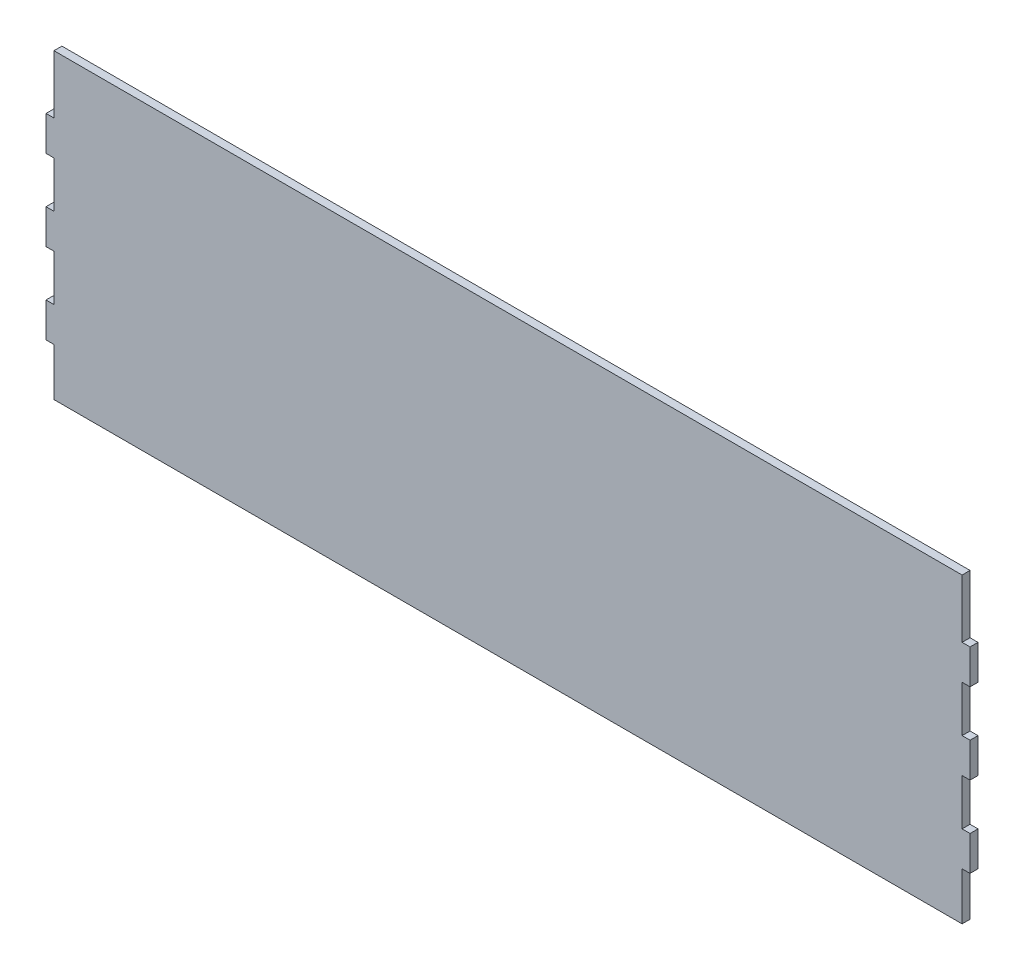
SolidWorks part; units mm, degrees
ref_plane "Front Plane" through (0, 0, 0) normal (0, 0, 1) x (1, 0, 0)
ref_plane "Top Plane" through (0, 0, 0) normal (0, 1, 0) x (1, 0, 0)
ref_plane "Right Plane" through (0, 0, 0) normal (1, 0, 0) x (0, 0, -1)
sketch "Croquis1" plane through (0, 0, 0) normal (0, 0, 1) x (1, 0, 0)
  line L1 (-174.32, 55) -> (174.32, 55)
  line L2 (-174.32, 55) -> (-174.32, -55)
  line L3 (-174.32, -55) -> (174.32, -55)
  line L4 (174.32, 55) -> (174.32, -55)
  line L5 (-174.32, 55) -> (174.32, -55) construction
  line L6 (-174.32, -55) -> (174.32, 55) construction
  point P0 (0, 0)
  dimension "D1" = 348.64
  dimension "D2" = 110
extrude "Saliente-Extruir1" add sketch "Croquis1" along normal blind 3
sketch "Croquis2" plane through (0, 0, 3) normal (0, 0, 1) x (1, 0, 0)
  line L0 (-174.32, 55) -> (-174.32, -55) construction
  line L1 (-174.32, 37) -> (-171.32, 37)
  line L2 (-174.32, 37) -> (-174.32, 23.9518)
  line L3 (-174.32, 23.9518) -> (-171.32, 23.9518)
  line L6 (-174.32, 6.5241) -> (-174.32, -6.5241)
  line L8 (-174.32, 6.5241) -> (-171.32, 6.5241)
  line L10 (-174.32, -6.5241) -> (-171.32, -6.5241)
  line L11 (-174.32, -23.9518) -> (-174.32, -37)
  line L12 (-174.32, -23.9518) -> (-171.32, -23.9518)
  line L14 (-174.32, -37) -> (-171.32, -37)
  line L15 (-174.32, -55) -> (174.32, -55) construction
  line L16 (174.32, 55) -> (-174.32, 55) construction
  line L17 (0, -55) -> (0, 55) construction
  line L18 (174.32, -23.9518) -> (171.32, -23.9518)
  line L19 (-171.32, -52) -> (171.32, -52)
  line L20 (171.32, -52) -> (171.32, 52)
  line L21 (-171.32, 52) -> (-171.32, -52)
  line L22 (171.32, 52) -> (-171.32, 52)
  line L24 (171.32, -52) -> (171.32, -37)
  line L25 (-171.32, 52) -> (-171.32, 37)
  line L28 (174.32, -37) -> (171.32, -37)
  line L29 (174.32, -23.9518) -> (174.32, -37)
  line L30 (174.32, 6.5241) -> (171.32, 6.5241)
  line L32 (174.32, -6.5241) -> (171.32, -6.5241)
  line L33 (174.32, 6.5241) -> (174.32, -6.5241)
  line L34 (174.32, 23.9518) -> (171.32, 23.9518)
  line L36 (174.32, 37) -> (171.32, 37)
  line L37 (174.32, 37) -> (174.32, 23.9518)
  line L38 (-171.32, 23.9518) -> (-171.32, 6.5241)
  line L39 (-171.32, -6.5241) -> (-171.32, -23.9518)
  line L40 (-171.32, -37) -> (-171.32, -52)
  line L41 (171.32, -23.9518) -> (171.32, -6.5241)
  line L42 (171.32, 6.5241) -> (171.32, 23.9518)
  line L43 (171.32, 37) -> (171.32, 52)
  line L44 (-171.32, 52) -> (-171.32, 55)
  line L45 (171.32, 52) -> (171.32, 55)
  line L46 (-171.32, -52) -> (-171.32, -55)
  line L47 (171.32, -52) -> (171.32, -55)
  line L48 (-171.32, -55) -> (171.32, -55)
  line L49 (-171.32, 55) -> (171.32, 55)
  line M3 (174.32, -55) -> (174.32, 55)
  line M4 (174.32, 55) -> (-174.32, 55)
  line M5 (-174.32, 55) -> (-174.32, -55)
  line M6 (-174.32, -55) -> (174.32, -55)
  dimension "D3" = 18
  dimension "D4" = 18
  dimension "D1" = 3
  dimension "D2" = 3
extrude "Cortar-Extruir1" cut sketch "Croquis2" against normal blind 3 contours L25 L44 L1 M4 M5 | L38 L3 L8 M5 | L45 L43 L36 M3 M4 | L42 L30 L34 M3 | L41 L18 L32 M3 | L24 L47 L28 M6 M3 | L39 L10 L12 M5 | L46 L40 L14 M5 M6
sketch "Croquis4" plane through (0, 0, 0) normal (0, 0, -1) x (-1, 0, 0)
  line L6 (171.32, 55) -> (171.32, 37) construction
  line L7 (-171.32, 55) -> (171.32, 55)
  line L8 (-171.32, 55) -> (-171.32, 59)
  line L9 (-171.32, 59) -> (171.32, 59)
  line L10 (171.32, 55) -> (171.32, 59)
  dimension "D1" = 4
extrude "Saliente-Extruir3" add sketch "Croquis4" against normal blind 3
sketch "Croquis6" plane through (0, 0, 0) normal (0, 0, -1) x (-1, 0, 0)
  line L0 (-175, -10.7078) -> (175, -10.7078) construction
  text T0 "ITAM " font "Century Gothic" height 25
  point P2 (0, -10.7078)
  dimension "D1" = 350
extrude "Cortar-Extruir4" cut sketch "Croquis6" against normal blind 1.5
